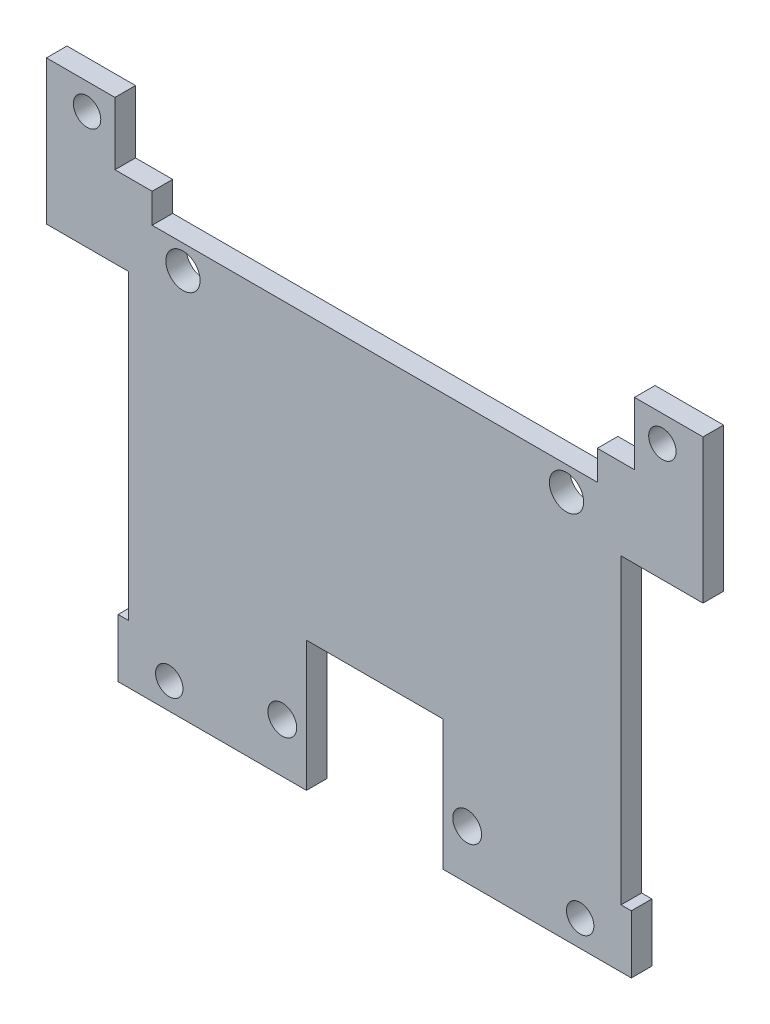
SolidWorks part; units mm, degrees
ref_plane "前视基准面" through (0, 0, 0) normal (0, 0, 1) x (1, 0, 0)
ref_plane "上视基准面" through (0, 0, 0) normal (0, 1, 0) x (1, 0, 0)
ref_plane "右视基准面" through (0, 0, 0) normal (1, 0, 0) x (0, 0, -1)
sketch "草图2" plane through (0, 0, 0) normal (0, 0, 1) x (1, 0, 0)
  line L0 (0, 0) -> (0, 52.9265) construction
  line L1 (32.5, 23.375) -> (-32.5, 23.375)
  line L2 (-32.5, 23.375) -> (-32.5, 27.675)
  line L3 (-32.5, 27.675) -> (-37.93, 27.675)
  line L4 (-37.93, 27.675) -> (-37.93, 36.825)
  line L5 (-37.93, 36.825) -> (-47.93, 36.825)
  line L6 (-47.93, 36.825) -> (-47.93, 15.805)
  line L7 (-47.93, 15.805) -> (-35.97, 15.805)
  line L8 (-35.97, 15.805) -> (-35.97, -28.325)
  line L9 (-35.97, -28.325) -> (-37.47, -28.325)
  line L10 (-37.47, -28.325) -> (-37.47, -36.825)
  line L11 (-37.47, -36.825) -> (-9.97, -36.825)
  line L12 (-9.97, -36.825) -> (-9.97, -17.825)
  line L13 (-9.97, -17.825) -> (9.97, -17.825)
  line L14 (0, 0) -> (0, -22.0326) construction
  line L15 (9.97, -36.825) -> (9.97, -17.825)
  line L16 (37.47, -36.825) -> (9.97, -36.825)
  line L17 (37.47, -28.325) -> (37.47, -36.825)
  line L18 (35.97, -28.325) -> (37.47, -28.325)
  line L19 (35.97, 15.805) -> (35.97, -28.325)
  line L20 (47.93, 15.805) -> (35.97, 15.805)
  line L21 (47.93, 36.825) -> (47.93, 15.805)
  line L22 (37.93, 36.825) -> (47.93, 36.825)
  line L23 (37.93, 27.675) -> (37.93, 36.825)
  line L24 (32.5, 27.675) -> (37.93, 27.675)
  line L25 (32.5, 23.375) -> (32.5, 27.675)
  point P20 (0, -17.825)
  point P31 (0, 23.375)
  dimension "D1" = 32.5
  dimension "D2" = 4.3
  dimension "D3" = 5.43
  dimension "D4" = 9.15
  dimension "D5" = 10
  dimension "D6" = 21.02
  dimension "D7" = 11.96
  dimension "D8" = 44.13
  dimension "D9" = 1.5
  dimension "D10" = 8.5
  dimension "D11" = 27.5
  dimension "D12" = 19
  dimension "D13" = 36.825
extrude "凸台-拉伸1" add sketch "草图2" along normal blind 3
sketch "草图3" plane through (0, 0, 3) normal (0, 0, 1) x (1, 0, 0)
  line L0 (0, 0) -> (0, 35.8477) construction
  line L1 (32.5, 23.375) -> (-32.5, 23.375) construction
  circle A0 centre (-28, 19.875) radius 2.5
  circle A1 centre (-13.5, -29.625) radius 2.1
  circle A2 centre (13.5, -29.625) radius 2.1
  circle A3 centre (28, 19.875) radius 2.5
  dimension "D1" = 3.5
  dimension "D2" = 28
  dimension "D3" = 5
  dimension "D4" = 49.5
  dimension "D5" = 13.5
  dimension "D6" = 4.2
extrude "切除-拉伸1" cut sketch "草图3" against normal through all
sketch "草图4" plane through (0, 0, 3) normal (0, 0, 1) x (1, 0, 0)
  line L0 (0, 0) -> (0, 45.0589) construction
  circle A0 centre (-42, 33) radius 2
  circle A1 centre (-30, -33) radius 2
  circle A2 centre (30, -33) radius 2
  circle A3 centre (42, 33) radius 2
  dimension "D1" = 42
  dimension "D2" = 33
  dimension "D3" = 30
  dimension "D4" = 33
extrude "切除-拉伸2" cut sketch "草图4" against normal blind 10
